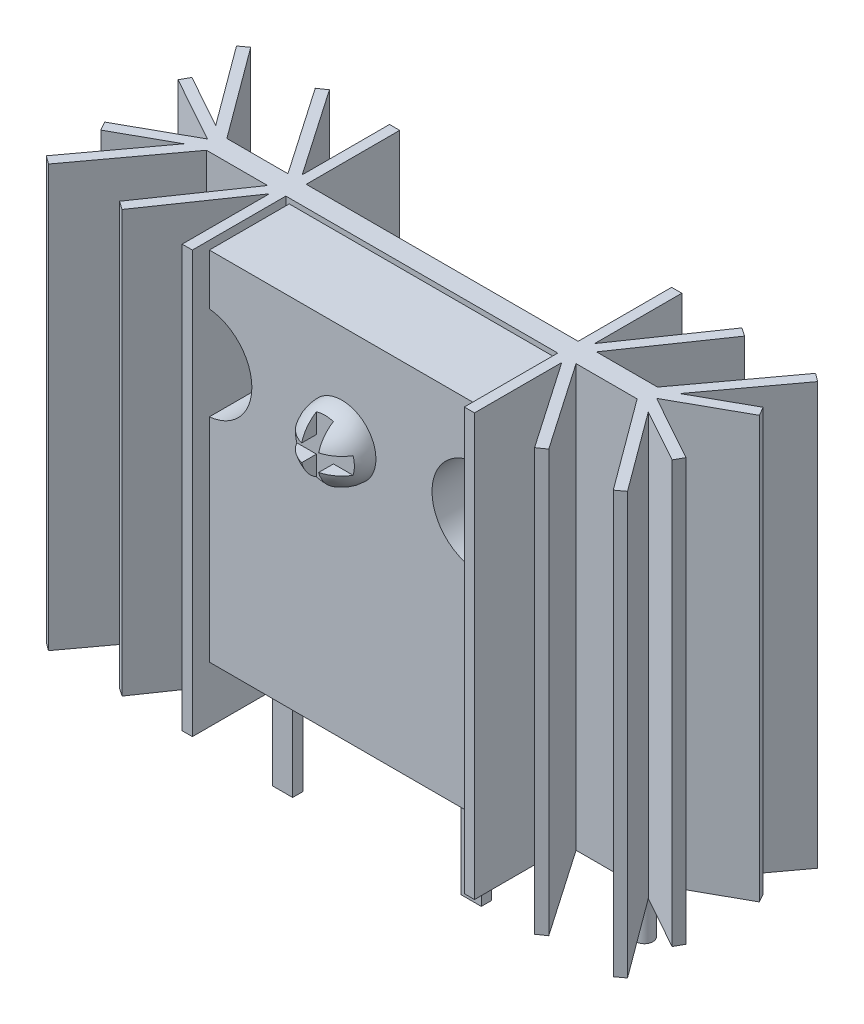
SolidWorks part; units mm, degrees
ref_plane "Alzado" through (0, 0, 0) normal (0, 0, 1) x (1, 0, 0)
ref_plane "Planta" through (0, 0, 0) normal (0, 1, 0) x (1, 0, 0)
ref_plane "Vista lateral" through (0, 0, 0) normal (1, 0, 0) x (0, 0, -1)
sketch "Croquis1" plane through (0, 0, 0) normal (0, 0, 1) x (1, 0, 0)
  line L1 (-12.9, 24.8) -> (12.9, 24.8)
  line L2 (-12.9, 24.8) -> (-12.9, 0)
  line L3 (-12.9, 0) -> (12.9, 0)
  line L4 (12.9, 24.8) -> (12.9, 0)
  line L5 (-12.9, 24.8) -> (12.9, 0) construction
  line L6 (-12.9, 0) -> (12.9, 24.8) construction
  point P0 (0, 12.4)
  point P5 (0, 0)
  dimension "D1" = 25.8
  dimension "D2" = 24.8
extrude "Saliente-Extruir1" add sketch "Croquis1" against normal blind 1.2
sketch "Croquis2" plane through (0, 0, 0) normal (0, 0, 1) x (1, 0, 0)
  line L0 (0, 0) -> (0, 24.8) construction
  line L1 (12.9, 24.8) -> (-12.9, 24.8) construction
  line L2 (-12.9, 0) -> (12.9, 0) construction
  line L3 (8, 24.8) -> (8.6, 24.8)
  line L4 (8, 24.8) -> (8, 0)
  line L5 (8, 0) -> (8.6, 0)
  line L6 (8.6, 24.8) -> (8.6, 0)
  line L7 (-8, 0) -> (-8.6, 0) construction
  line L8 (-8.6, 24.8) -> (-8.6, 0) construction
  line L9 (-8, 24.8) -> (-8.6, 24.8) construction
  line L10 (-8, 24.8) -> (-8, 0) construction
  dimension "D1" = 16
  dimension "D2" = 0.6
extrude "Saliente-Extruir2" add sketch "Croquis2" along normal blind 5.5
ref_plane "Plano1" through (0, 0, -0.6) normal (0, 0, 1) x (1, 0, 0)
sketch "Croquis3" plane through (0, 24.8, 0) normal (0, 1, 0) x (1, 0, 0)
  line L0 (-12.9, 1.2) -> (-12.9, 0) construction
  line L1 (-17.1, 6.7) -> (17.1, 6.7) construction
  line L2 (-17.1, 6.7) -> (-17.1, -5.5) construction
  line L3 (-17.1, -5.5) -> (17.1, -5.5) construction
  line L4 (17.1, 6.7) -> (17.1, -5.5) construction
  line L5 (-17.1, 6.7) -> (17.1, -5.5) construction
  line L6 (-17.1, -5.5) -> (17.1, 6.7) construction
  line L7 (8.17, 0.2597) -> (12.1358, -5.5)
  line L8 (0, 0.6) -> (12.6, 0.6) construction
  line L9 (8.17, 0.2597) -> (8.6642, 0.6)
  line L10 (0, -5.5) -> (0, 6.7) construction
  line L11 (8.3, 6.7) -> (8.3, -5.5) construction
  line L12 (8.6, -5.5) -> (8, -5.5) construction
  line L13 (8.3, 0.6) -> (12.5, -5.5) construction
  line L14 (8, -5.5) -> (8, 0) construction
  line L15 (12.6, 0.6) -> (17.1, -5.5) construction
  line L16 (12.6, 0.6) -> (17.1, -1.9) construction
  line L17 (12.9, 1.2) -> (12.9, 0) construction
  line L18 (12.1358, -5.5) -> (12.63, -5.1597)
  line L19 (8.6642, 0.6) -> (12.63, -5.1597)
  line L20 (12.2272, 0.6) -> (16.6172, -5.3508)
  line L21 (12.2272, 0.6) -> (12.71, 0.9562)
  line L22 (16.6172, -5.3508) -> (17.1, -4.9947)
  line L23 (12.71, 0.9562) -> (12.8027, 0.8306)
  line L24 (13.6607, -0.3324) -> (16.8086, -2.0813)
  line L26 (16.8086, -2.0813) -> (17.1, -1.5568)
  line L27 (12.8027, 0.8306) -> (17.1, -1.5568)
  line L28 (13.6607, -0.3324) -> (17.1, -4.9947)
  point P0 (0, 0.6)
  point P5 (0, 6.7)
  point P9 (-12.9, 0.6)
  point P10 (-17.1, 0.6)
  point P15 (0, 0.6)
  point P17 (12.3829, -5.3299)
  point P29 (16.9543, -1.8191)
  point P41 (16.8586, -5.1727)
  dimension "D1" = 34.2
  dimension "D2" = 4.5
  dimension "D3" = 2.5
  dimension "D4" = 0.3
  dimension "D5" = 0.6
  dimension "D6" = 0.6
  dimension "D7" = 0.6
extrude "Saliente-Extruir3" add sketch "Croquis3" against normal up to surface (24.8 mm away) up to face at (4.15, 0, 1.075)
mirror "Simetría1" about plane through (0, 0, -0.6) normal (0, 0, 1) of "Saliente-Extruir3", "Saliente-Extruir2"
mirror "Simetría2" about plane through (0, 0, 0) normal (1, 0, 0) of "Simetría1", "Saliente-Extruir2", "Saliente-Extruir3"
sketch "Croquis4" plane through (0, 0, 0) normal (0, -1, 0) x (1, 0, 0)
  line L0 (0, 0) -> (0, -1.2) construction
  line L1 (-8, -1.2) -> (8, -1.2) construction
  circle A0 centre (12.5, -0.6) radius 0.5
  circle A1 centre (-12.5, -0.6) radius 0.5
  dimension "D1" = 1
  dimension "D2" = 25
extrude "Saliente-Extruir4" add sketch "Croquis4" along normal blind 3
sketch "Croquis5" plane through (0, 0, 0) normal (0, 0, 1) x (1, 0, 0)
  line L0 (-8, 0) -> (8, 0) construction
  line L1 (-7.8, 24.5) -> (7.8, 24.5)
  line L2 (-7.8, 24.5) -> (-7.8, 21.5)
  line L3 (-7.8, 3.5) -> (7.8, 3.5)
  line L4 (7.8, 24.5) -> (7.8, 21.5)
  line L5 (-7.8, 24.5) -> (7.8, 3.5) construction
  line L6 (-7.8, 3.5) -> (7.8, 24.5) construction
  line L7 (0, 3.5) -> (0, 24.5) construction
  line L8 (-7.8, 16) -> (-7.8, 3.5)
  line L9 (7.8, 16) -> (7.8, 3.5)
  arc A0 (-7.8, 21.5) -> (-7.8, 16) centre (-8.0625, 18.75) cw
  arc A1 (7.8, 21.5) -> (7.8, 16) centre (8.0625, 18.75) ccw
  point P0 (0, 14)
  point P19 (-5.3, 18.75)
  dimension "D1" = 15.6
  dimension "D2" = 3.5
  dimension "D3" = 21
  dimension "D4" = 3
  dimension "D5" = 5.5
  dimension "D6" = 2.5
extrude "Saliente-Extruir5" add sketch "Croquis5" along normal blind 4.7 separate body
sketch "Croquis6" plane through (0, 3.5, 0) normal (0, -1, 0) x (1, 0, 0)
  line L0 (7.8, 4.7) -> (7.8, 0) construction
  line L1 (-6.15, 2.65) -> (-4.95, 2.65)
  line L2 (-6.15, 2.65) -> (-6.15, 2.05)
  line L3 (-6.15, 2.05) -> (-4.95, 2.05)
  line L4 (-4.95, 2.65) -> (-4.95, 2.05)
  line L5 (-6.15, 2.65) -> (-4.95, 2.05) construction
  line L6 (-6.15, 2.05) -> (-4.95, 2.65) construction
  line L7 (0, 0) -> (0, 4.7) construction
  line L8 (-7.8, 4.7) -> (7.8, 4.7) construction
  line L9 (6.15, 2.05) -> (4.95, 2.05)
  line L10 (4.95, 2.65) -> (4.95, 2.05)
  line L11 (6.15, 2.65) -> (4.95, 2.65)
  line L12 (6.15, 2.65) -> (6.15, 2.05)
  point P0 (-5.55, 2.35)
  point P8 (7.8, 2.35)
  dimension "D1" = 12.3
  dimension "D2" = 1.2
  dimension "D3" = 0.6
extrude "Saliente-Extruir6" add sketch "Croquis6" along normal up to surface (6.5 mm away) separate body up to face at (-13, -3, -0.6)
sketch "Croquis7" plane through (0, 0, 0) normal (1, 0, 0) x (0, 0, -1)
  line L0 (-4.7, 18.75) -> (-6.7, 18.75)
  line L1 (-4.7, 21.5) -> (-4.7, 16) construction
  line L2 (-4.7, 18.75) -> (-4.7, 20.75)
  arc A0 (-6.7, 18.75) -> (-4.7, 20.75) centre (-4.7, 18.75) cw
  dimension "D1" = 2
revolve "Revolución1" add sketch "Croquis7" angle 360 about L0
ref_plane "Plano2" through (0, 0, 6.7) normal (0, 0, 1) x (1, 0, 0)
sketch "Croquis8" plane through (0, 0, 6.7) normal (0, 0, 1) x (1, 0, 0)
  line L0 (0.5, 18.25) -> (1.9365, 18.25)
  line L1 (-0.5, 20.6865) -> (0.5, 20.6865)
  line L2 (-0.5, 20.6865) -> (-0.5, 19.25)
  line L3 (-0.5, 16.8135) -> (0.5, 16.8135)
  line L4 (0.5, 20.6865) -> (0.5, 19.25)
  line L5 (-0.5, 20.6865) -> (0.5, 16.8135) construction
  line L6 (-0.5, 16.8135) -> (0.5, 20.6865) construction
  line L7 (-1.9365, 19.25) -> (-0.5, 19.25)
  line L8 (-1.9365, 19.25) -> (-1.9365, 18.25)
  line L9 (-1.9365, 18.25) -> (-0.5, 18.25)
  line L10 (1.9365, 19.25) -> (1.9365, 18.25)
  line L11 (-1.9365, 19.25) -> (1.9365, 18.25) construction
  line L12 (-1.9365, 18.25) -> (1.9365, 19.25) construction
  line L13 (-0.5, 18.25) -> (-0.5, 16.8135)
  line L14 (0.5, 18.25) -> (0.5, 16.8135)
  line L15 (0.5, 19.25) -> (1.9365, 19.25)
  circle A1 centre (0, 18.75) radius 2
  circle A2 centre (0, 18.75) radius 2 construction
  dimension "D2" = 1
  dimension "D3" = 1
  dimension "D1" = 0
extrude "Cortar-Extruir1" cut sketch "Croquis8" against normal blind 1
